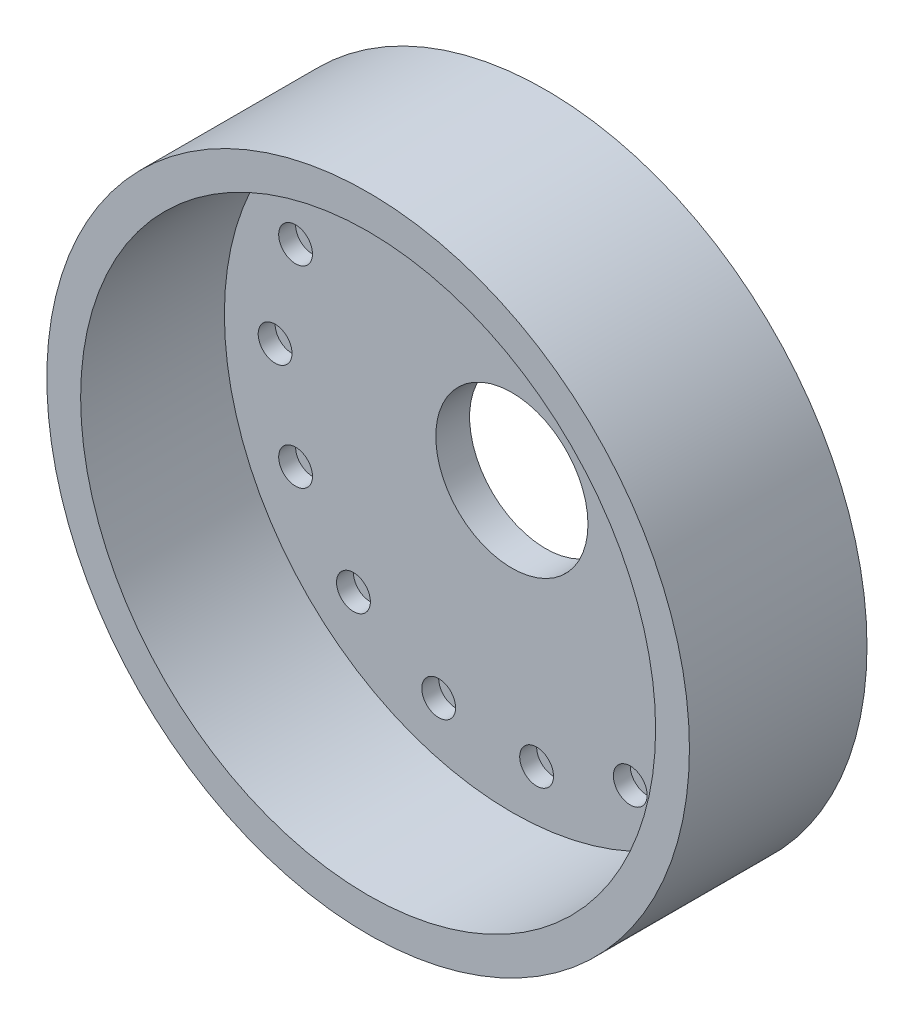
SolidWorks part; units mm, degrees
ref_plane "Front Plane" through (0, 0, 0) normal (0, 0, 1) x (1, 0, 0)
ref_plane "Top Plane" through (0, 0, 0) normal (0, 1, 0) x (1, 0, 0)
ref_plane "Right Plane" through (0, 0, 0) normal (1, 0, 0) x (0, 0, -1)
sketch "Sketch1" plane through (0, 0, 0) normal (0, 0, 1) x (1, 0, 0)
  circle A0 centre (0, 0) radius 60.325
  dimension "D1" = 120.65
extrude "Boss-Extrude1" add sketch "Sketch1" along normal blind 33.3375
sketch "Sketch2" plane through (0, 0, 33.3375) normal (0, 0, 1) x (1, 0, 0)
  line L0 (0, 0) -> (-96.755, 0) construction
  circle A0 centre (0, 0) radius 53.975
  circle A1 centre (0, 0) radius 60.325 construction
  dimension "D1" = 6.35
extrude "Cut-Extrude1" cut sketch "Sketch2" against normal offset from surface (26.9875 mm away) 6.35 up to face at (60.325, 0, 0)
sketch "Sketch3" plane through (0, 0, 6.35) normal (0, 0, 1) x (1, 0, 0)
  line L0 (1.0369, 0) -> (-103.1353, 0) construction
  circle A0 centre (0, 0) radius 44.45 construction
  circle A1 centre (-44.45, 0) radius 3.175
  circle A2 centre (-40.6071, 18.0794) radius 3.175
  circle A3 centre (-29.7429, 33.0328) radius 3.175
  circle A4 centre (-13.7358, 42.2745) radius 3.175
  circle A5 centre (4.6463, 44.2065) radius 3.175
  circle A6 centre (22.225, 38.4948) radius 3.175
  circle A7 centre (35.9608, 26.1271) radius 3.175
  circle A8 centre (43.4787, 9.2417) radius 3.175
  circle A9 centre (43.4787, -9.2417) radius 3.175
  circle A10 centre (35.9608, -26.1271) radius 3.175
  circle A11 centre (22.225, -38.4948) radius 3.175
  circle A12 centre (4.6463, -44.2065) radius 3.175
  circle A13 centre (-13.7358, -42.2745) radius 3.175
  circle A14 centre (-29.7429, -33.0328) radius 3.175
  circle A15 centre (-40.6071, -18.0794) radius 3.175
  point P37 (0, 0)
  dimension "D1" = 88.9
  dimension "D2" = 6.35
  dimension "D3" = 15
extrude "Cut-Extrude2" cut sketch "Sketch3" against normal blind 3.175
sketch "Sketch4" plane through (0, 0, 6.35) normal (0, 0, 1) x (1, 0, 0)
  circle A0 centre (0, 0) radius 14.2875
  dimension "D1" = 28.575
extrude "Cut-Extrude3" cut sketch "Sketch4" against normal through all
